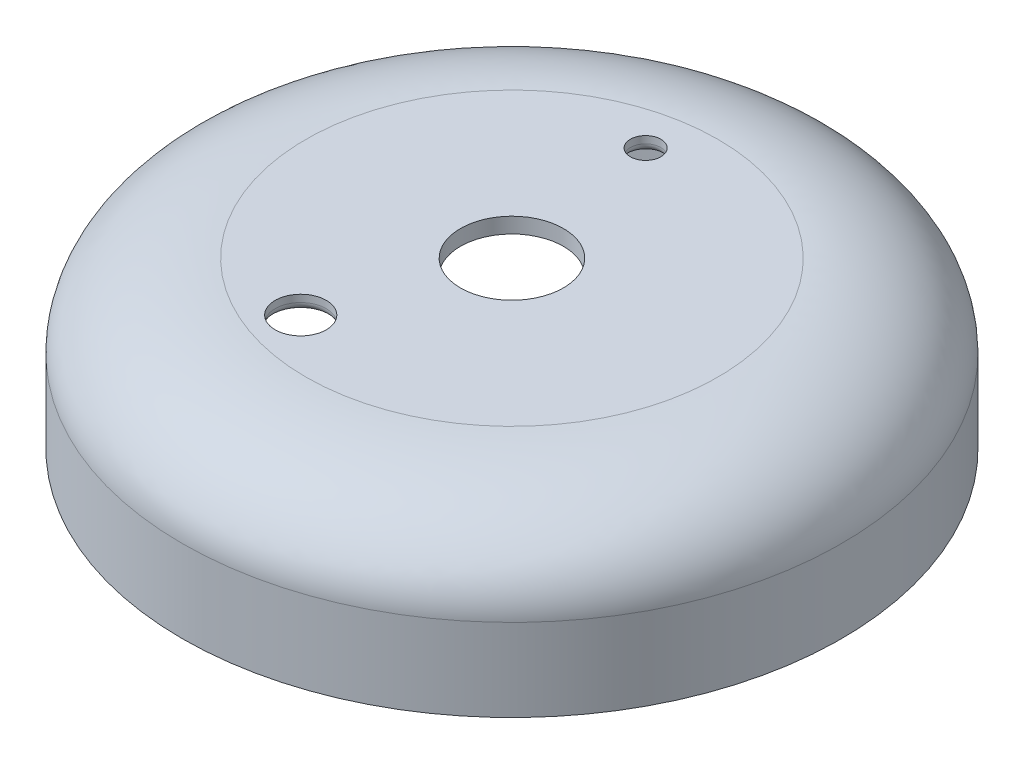
SolidWorks part; units mm, degrees
material "6061-T6 (SS)"
ref_plane "Front" through (0, 0, 0) normal (0, 0, 1) x (1, 0, 0)
ref_plane "Top" through (0, 0, 0) normal (0, 1, 0) x (1, 0, 0)
ref_plane "Right" through (0, 0, 0) normal (1, 0, 0) x (0, 0, -1)
sketch "Sketch1" plane through (0, 0, 0) normal (0, 0, 1) x (1, 0, 0)
  line L0 (0, 0) -> (101.6, 0) construction
  line L1 (101.6, 0) -> (101.6, -67.9188) construction
  line L2 (0, 29.5111) -> (0, -26.7187) construction
  line L3 (0, 0) -> (0, -4.7625)
  line L4 (0, 0) -> (63.5, 0)
  line L5 (0, -4.7625) -> (63.5, -4.7625)
  line L6 (101.6, 5.9654) -> (96.8375, 5.9654) construction
  line L7 (96.8375, 5.9654) -> (96.8375, -58.8285) construction
  line L9 (63.5, -25.4) -> (127.5739, -25.4) construction
  line L12 (63.5, 0) -> (63.5, -38.8167) construction
  line L14 (96.8375, -50.8) -> (101.6, -50.8)
  line L15 (101.6, -50.8) -> (101.6, -25.4)
  line L16 (96.8375, -50.8) -> (96.8375, -25.4)
  ellipse E0 centre (63.5, -25.4) end of major axis (96.8375, -25.4) minor radius 20.6375 (96.8375, -25.4) -> (63.5, -4.7625) ccw
  ellipse E1 centre (63.5, -25.4) end of major axis (25.4, -25.4) minor radius 25.4 (63.5, 0) -> (101.6, -25.4) cw
  dimension "D1" = 101.6
  dimension "D2" = 63.5
  dimension "D3" = 25.4
  dimension "D4" = 4.7625
  dimension "D5" = 4.7625
  dimension "D6" = 25.4
revolve "Revolve1" add sketch "Sketch1" angle 360 about L2
sketch "Sketch2" plane through (0, 0, 0) normal (0, 1, 0) x (1, 0, 0)
  line L0 (0, 0) -> (-68.318, -187.7022) construction
  line L1 (0, 0) -> (303.3008, 0) construction
  line L2 (0, 0) -> (-28.4694, 161.4578) construction
  circle A0 centre (-17.3746, -47.7364) radius 7.874
  circle A1 centre (0, 0) radius 15.875
  circle A2 centre (-8.8213, 50.0282) radius 4.699
  dimension "D1" = 15.748
  dimension "D3" = 31.75
  dimension "D5" = 50.8
  dimension "D6" = 9.398
  dimension "D2" = 50.8
  dimension "D4" = 250
  dimension "D7" = 100
extrude "Cut-Extrude1" cut sketch "Sketch2" against normal blind 25.4
fillet "Fillet1" radius 2.54 2 edges at (-17.3746, -4.7625, 55.6104) (-8.8213, -4.7625, -45.3292)
